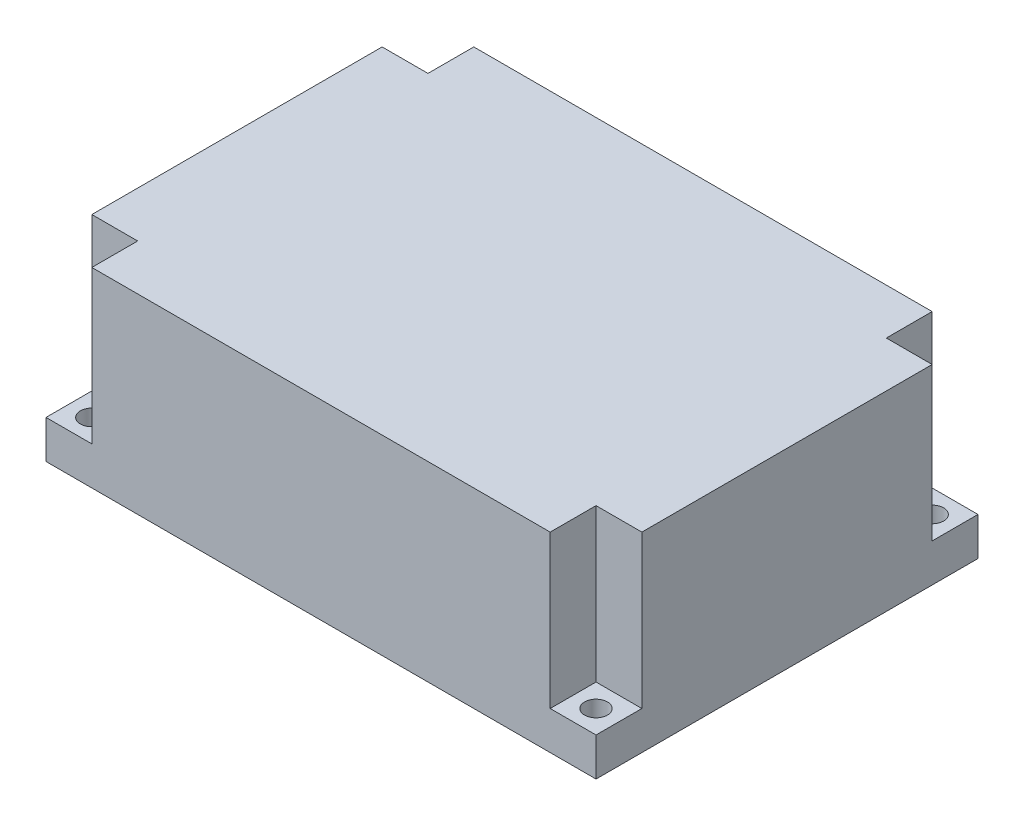
SolidWorks part; units mm, degrees
ref_plane "前视基准面" through (0, 0, 0) normal (0, 0, 1) x (1, 0, 0)
ref_plane "上视基准面" through (0, 0, 0) normal (0, 1, 0) x (1, 0, 0)
ref_plane "右视基准面" through (0, 0, 0) normal (1, 0, 0) x (0, 0, -1)
sketch "草图1" plane through (0, 0, 0) normal (0, 1, 0) x (1, 0, 0)
  line L5 (-36, -25) -> (36, -25)
  line L6 (-36, -25) -> (-36, 25)
  line L7 (-36, 25) -> (36, 25)
  line L8 (36, -25) -> (36, 25)
  line L9 (-36, -25) -> (36, 25) construction
  line L10 (-36, 25) -> (36, -25) construction
  point P0 (0, 0)
  dimension "D1" = 72
  dimension "D2" = 50
extrude "凸台-拉伸1" add sketch "草图1" along normal blind 25
sketch "草图3" plane through (0, 25, 0) normal (0, 1, 0) x (1, 0, 0)
  line L0 (-39.988, 0) -> (48.0235, 0) construction
  line L1 (0, 30.7445) -> (0, -31.0275) construction
  line L2 (36, 25) -> (-36, 25) construction
  line L3 (-36, 25) -> (-36, -25) construction
  circle A0 centre (-33, 22) radius 1.5
  circle A1 centre (33, 22) radius 1.5
  circle A2 centre (33, -22) radius 1.5
  circle A3 centre (-33, -22) radius 1.5
  dimension "D1" = 3
  dimension "D2" = 3
  dimension "D3" = 3
extrude "切除-拉伸1" cut sketch "草图3" against normal through all
sketch "草图4" plane through (0, 25, 0) normal (0, 1, 0) x (1, 0, 0)
  line L1 (-36, 25) -> (-30, 25)
  line L2 (-36, 25) -> (-36, 19)
  line L3 (-36, 19) -> (-30, 19)
  line L4 (-30, 25) -> (-30, 19)
  line L5 (36, 25) -> (30, 25)
  line L6 (36, 25) -> (36, 19)
  line L7 (36, 19) -> (30, 19)
  line L8 (30, 25) -> (30, 19)
  line L9 (36, -25) -> (30, -25)
  line L10 (36, -25) -> (36, -19)
  line L11 (36, -19) -> (30, -19)
  line L12 (30, -25) -> (30, -19)
  line L13 (-36, -25) -> (-30, -25)
  line L14 (-36, -25) -> (-36, -19)
  line L15 (-36, -19) -> (-30, -19)
  line L16 (-30, -25) -> (-30, -19)
  dimension "D1" = 6
  dimension "D2" = 6
  dimension "D3" = 6
  dimension "D4" = 6
  dimension "D5" = 6
  dimension "D6" = 6
  dimension "D7" = 6
  dimension "D8" = 6
extrude "切除-拉伸2" cut sketch "草图4" against normal blind 20
